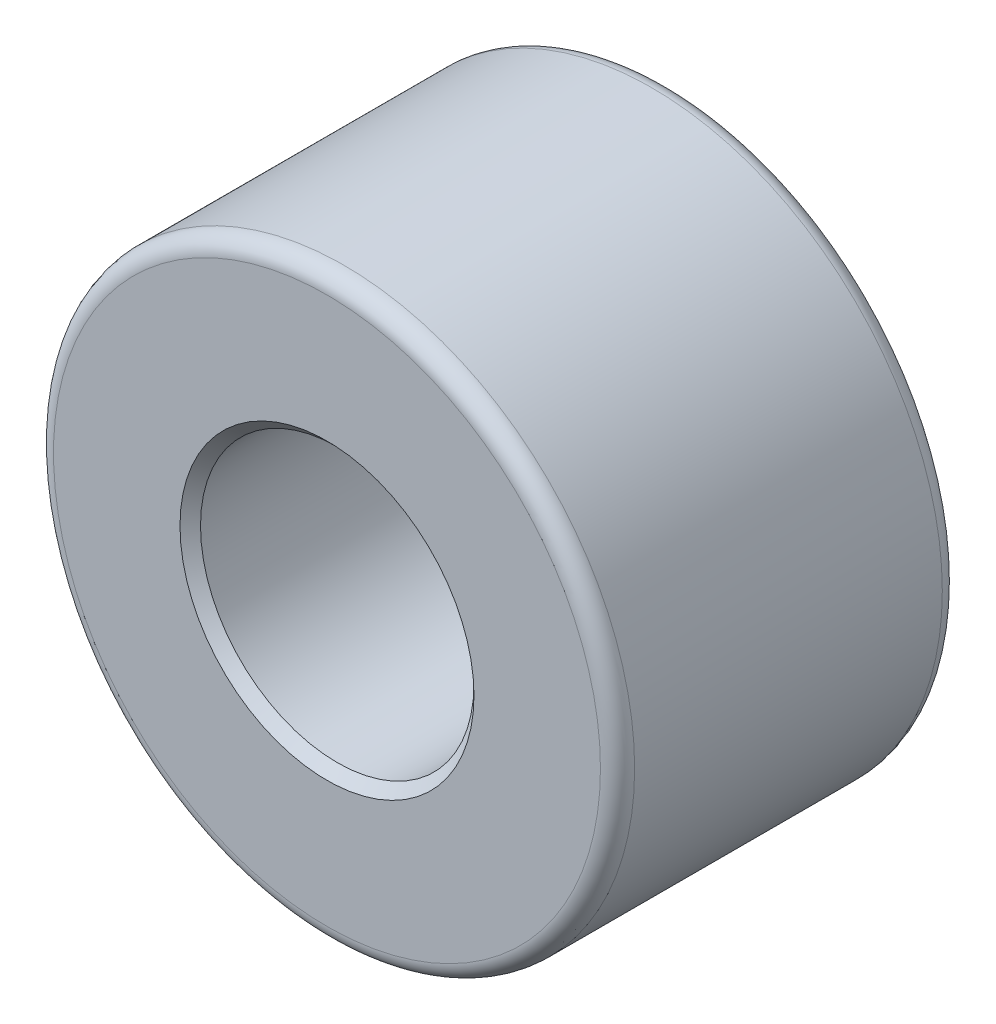
SolidWorks part; units mm, degrees
ref_plane "Front Plane" through (0, 0, 0) normal (0, 0, 1) x (1, 0, 0)
ref_plane "Top Plane" through (0, 0, 0) normal (0, 1, 0) x (1, 0, 0)
ref_plane "Right Plane" through (0, 0, 0) normal (1, 0, 0) x (0, 0, -1)
sketch "Sketch1" plane through (0, 0, 0) normal (0, 0, 1) x (1, 0, 0)
  circle A0 centre (0, 0) radius 8.5
  circle A1 centre (0, 0) radius 4
  dimension "D1" = 8
  dimension "D2" = 17
extrude "Boss-Extrude1" add sketch "Sketch1" along normal blind 10
fillet "Fillet1" radius 0.5 2 edges at (8.5, 0, 10) (8.5, 0, 0)
chamfer "Chamfer1" distance 0.3 angle 45 2 edges at (4, 0, 0) (4, 0, 10)
